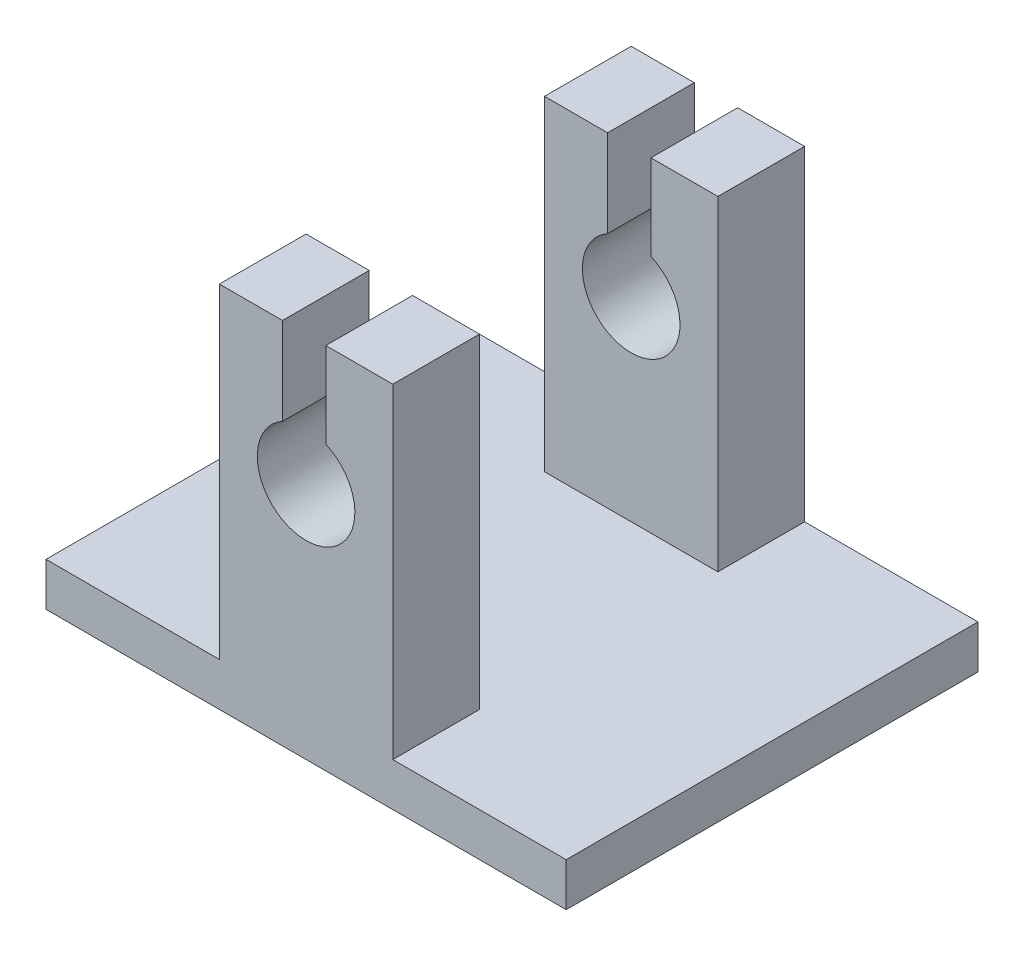
SolidWorks part; units mm, degrees
ref_plane "Front Plane" through (0, 0, 0) normal (0, 0, 1) x (1, 0, 0)
ref_plane "Top Plane" through (0, 0, 0) normal (0, 1, 0) x (1, 0, 0)
ref_plane "Right Plane" through (0, 0, 0) normal (1, 0, 0) x (0, 0, -1)
sketch "Sketch2" plane through (0, 0, 0) normal (0, 1, 0) x (1, 0, 0)
  line L1 (-76.2, -60.325) -> (76.2, -60.325)
  line L2 (-76.2, -60.325) -> (-76.2, 60.325)
  line L3 (-76.2, 60.325) -> (76.2, 60.325)
  line L4 (76.2, -60.325) -> (76.2, 60.325)
  line L5 (-76.2, -60.325) -> (76.2, 60.325) construction
  line L6 (-76.2, 60.325) -> (76.2, -60.325) construction
  point P0 (0, 0)
  dimension "D1" = 120.65
  dimension "D2" = 152.4
extrude "Boss-Extrude2" add sketch "Sketch2" along normal blind 12.7
sketch "Sketch4" plane through (0, 12.7, 0) normal (0, 1, 0) x (1, 0, 0)
  line L0 (-127, -60.325) -> (0, -60.325) construction
  line L1 (-76.2, -60.325) -> (76.2, -60.325) construction
  line L2 (0, -60.325) -> (0, -47.625) construction
  line L3 (0, -47.625) -> (25.4, -47.625) construction
  line L4 (25.4, -47.625) -> (25.4, -34.925) construction
  line L6 (-25.4, -60.325) -> (25.4, -60.325)
  line L7 (-25.4, -60.325) -> (-25.4, -34.925)
  line L8 (-25.4, -34.925) -> (25.4, -34.925)
  line L9 (25.4, -60.325) -> (25.4, -34.925)
  line L10 (-25.4, -60.325) -> (25.4, -34.925) construction
  line L11 (-25.4, -34.925) -> (25.4, -60.325) construction
  dimension "D1" = 12.7
  dimension "D2" = 25.4
  dimension "D3" = 12.7
extrude "Boss-Extrude3" add sketch "Sketch4" along normal blind 95.25
mirror "Mirror1" about plane through (0, 0, 0) normal (0, 0, 1) of "Boss-Extrude3"
sketch "Sketch6" plane through (0, 0, 60.325) normal (0, 0, 1) x (1, 0, 0)
  line L0 (-76.2, 0) -> (76.2, 0) construction
  line L1 (-25.4, 107.95) -> (25.4, 107.95) construction
  line L4 (-6.9118, 107.95) -> (5.7882, 107.95)
  line L5 (-6.9118, 107.95) -> (-6.9118, 82.3544)
  line L7 (5.7882, 107.95) -> (5.7882, 82.9125)
  arc A0 (-6.9118, 82.3544) -> (5.7882, 82.9125) centre (0, 69.85) ccw
  point P4 (-6.9118, 107.95)
  dimension "D1" = 28.575
  dimension "D2" = 69.85
  dimension "D3" = 12.7
extrude "Cut-Extrude1" cut sketch "Sketch6" against normal through all
